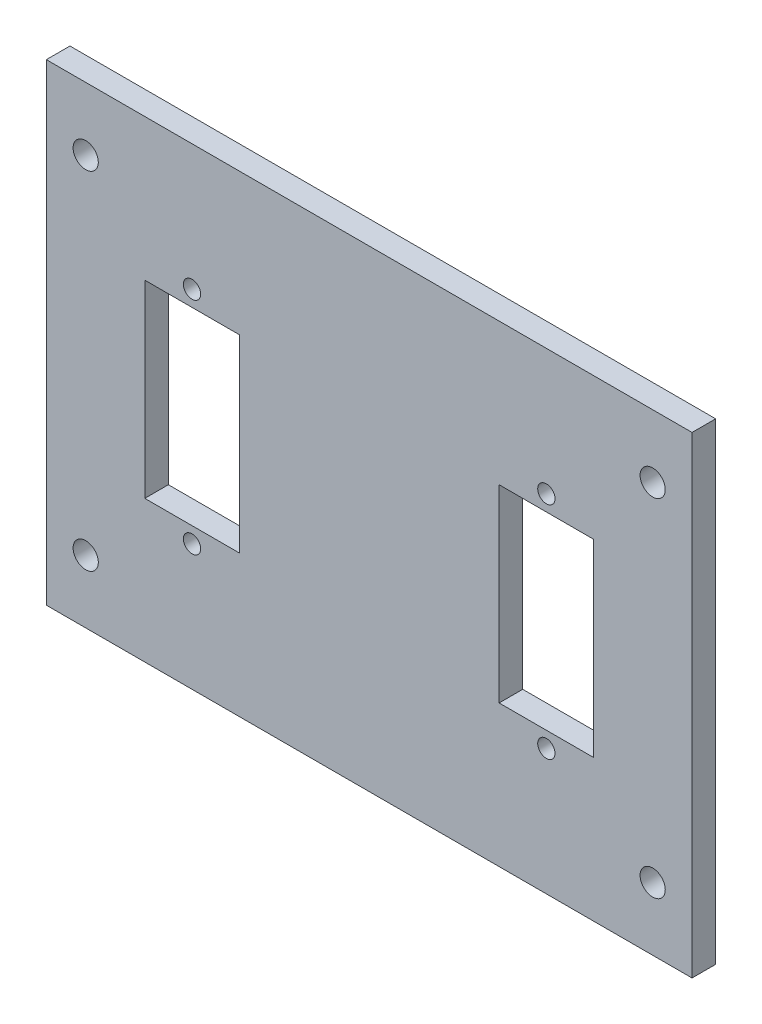
SolidWorks part; units mm, degrees
material "Thornel Mat VMA"
ref_plane "前视基准面" through (0, 0, 0) normal (0, 0, 1) x (1, 0, 0)
ref_plane "上视基准面" through (0, 0, 0) normal (0, 1, 0) x (1, 0, 0)
ref_plane "右视基准面" through (0, 0, 0) normal (1, 0, 0) x (0, 0, -1)
other "Configuration Table"
sketch "草图1" plane through (0, 0, 0) normal (0, 0, 1) x (1, 0, 0)
  line L0 (41, 0) -> (41, 68.3484) construction
  line L1 (0, 0) -> (82, 0)
  line L2 (0, 0) -> (0, 60)
  line L3 (0, 60) -> (82, 60)
  line L4 (82, 0) -> (82, 60)
  line L5 (0, 30) -> (53.9084, 30) construction
  line L6 (69.5, 42) -> (57.5, 42)
  line L7 (12.5, 18) -> (24.5, 18)
  line L8 (12.5, 18) -> (12.5, 42)
  line L9 (12.5, 42) -> (24.5, 42)
  line L10 (24.5, 18) -> (24.5, 42)
  line L11 (57.5, 18) -> (57.5, 42)
  line L12 (69.5, 18) -> (57.5, 18)
  line L13 (69.5, 18) -> (69.5, 42)
  line L14 (18.5, 42) -> (18.5, 35.2436) construction
  circle A0 centre (18.5, 44) radius 1.1
  circle A1 centre (18.5, 16) radius 1.1
  circle A2 centre (77, 8) radius 1.6
  circle A3 centre (5, 8) radius 1.6
  circle A4 centre (77, 52) radius 1.6
  circle A5 centre (5, 52) radius 1.6
  circle A6 centre (63.5, 16) radius 1.1
  circle A7 centre (63.5, 44) radius 1.1
  dimension "D6" = 2.2
  dimension "D8" = 3.2
  dimension "D1" = 82
  dimension "D2" = 60
  dimension "D3" = 24
  dimension "D4" = 12
  dimension "D5" = 28
  dimension "D7" = 5
  dimension "D9" = 8
  dimension "D10" = 45
extrude "凸台-拉伸1" add sketch "草图1" along normal blind 3
